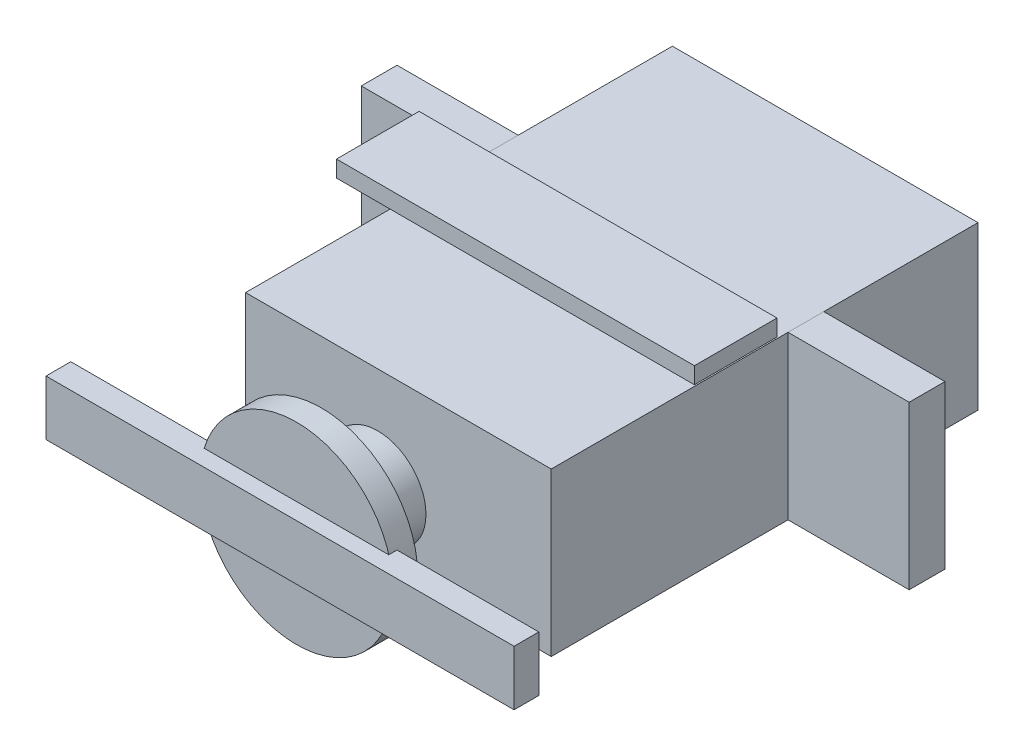
SolidWorks part; units mm, degrees
ref_plane "前视基准面" through (0, 0, 0) normal (0, 0, 1) x (1, 0, 0)
ref_plane "上视基准面" through (0, 0, 0) normal (0, 1, 0) x (1, 0, 0)
ref_plane "右视基准面" through (0, 0, 0) normal (1, 0, 0) x (0, 0, -1)
other "Configuration Table"
sketch "草图1" plane through (0, 0, 0) normal (0, 0, 1) x (1, 0, 0)
  line L1 (-11.1, -5.9) -> (11.1, -5.9)
  line L2 (-11.1, -5.9) -> (-11.1, 5.9)
  line L3 (-11.1, 5.9) -> (11.1, 5.9)
  line L4 (11.1, -5.9) -> (11.1, 5.9)
  line L5 (-11.1, -5.9) -> (11.1, 5.9) construction
  line L6 (-11.1, 5.9) -> (11.1, -5.9) construction
  point P0 (0, 0)
extrude "SG90 body - approx 22.2 x 11.8 x 31 mm" add sketch "草图1" along normal blind 31 from offset 15.5 separate body
sketch "草图2" plane through (0, 0, 0) normal (0, 0, 1) x (1, 0, 0)
  line L1 (-19.9, -5.9) -> (-11.1, -5.9)
  line L2 (-19.9, -5.9) -> (-19.9, 5.9)
  line L3 (-19.9, 5.9) -> (-11.1, 5.9)
  line L4 (-11.1, -5.9) -> (-11.1, 5.9)
  line L5 (-19.9, -5.9) -> (-11.1, 5.9) construction
  line L6 (-19.9, 5.9) -> (-11.1, -5.9) construction
  point P0 (-15.5, 0)
extrude "SG90 mounting ear left" add sketch "草图2" along normal blind 2.6 from offset 4.3 separate body
sketch "草图3" plane through (0, 0, 0) normal (0, 0, 1) x (1, 0, 0)
  line L1 (11.1, -5.9) -> (19.9, -5.9)
  line L2 (11.1, -5.9) -> (11.1, 5.9)
  line L3 (11.1, 5.9) -> (19.9, 5.9)
  line L4 (19.9, -5.9) -> (19.9, 5.9)
  line L5 (11.1, -5.9) -> (19.9, 5.9) construction
  line L6 (11.1, 5.9) -> (19.9, -5.9) construction
  point P0 (15.5, 0)
extrude "SG90 mounting ear right" add sketch "草图3" along normal blind 2.6 from offset 4.3 separate body
sketch "草图4" plane through (0, 0, 0) normal (0, 0, 1) x (1, 0, 0)
  circle A0 centre (0, 0) radius 3.5
extrude "servo spline hub" add sketch "草图4" along normal blind 3 from offset 17 separate body
sketch "草图5" plane through (0, 0, 0) normal (0, 0, 1) x (1, 0, 0)
  circle A0 centre (0, 0) radius 7
extrude "servo horn center" add sketch "草图5" along normal blind 1.8 from offset 21.1 separate body
sketch "草图6" plane through (0, 0, 0) normal (0, 0, 1) x (1, 0, 0)
  line L1 (-17, -2) -> (17, -2)
  line L2 (-17, -2) -> (-17, 2)
  line L3 (-17, 2) -> (17, 2)
  line L4 (17, -2) -> (17, 2)
  line L5 (-17, -2) -> (17, 2) construction
  line L6 (-17, 2) -> (17, -2) construction
  point P0 (0, 0)
extrude "servo horn arm" add sketch "草图6" along normal blind 1.8 from offset 22.3 separate body
sketch "草图7" plane through (0, 0, 0) normal (0, 0, 1) x (1, 0, 0)
  line L1 (-13, 7.9) -> (13, 7.9)
  line L2 (-13, 7.9) -> (-13, 9.1)
  line L3 (-13, 9.1) -> (13, 9.1)
  line L4 (13, 7.9) -> (13, 9.1)
  line L5 (-13, 7.9) -> (13, 9.1) construction
  line L6 (-13, 9.1) -> (13, 7.9) construction
  point P0 (0, 8.5)
extrude "servo label plate - SG90" add sketch "草图7" along normal blind 6 from offset 1 separate body
